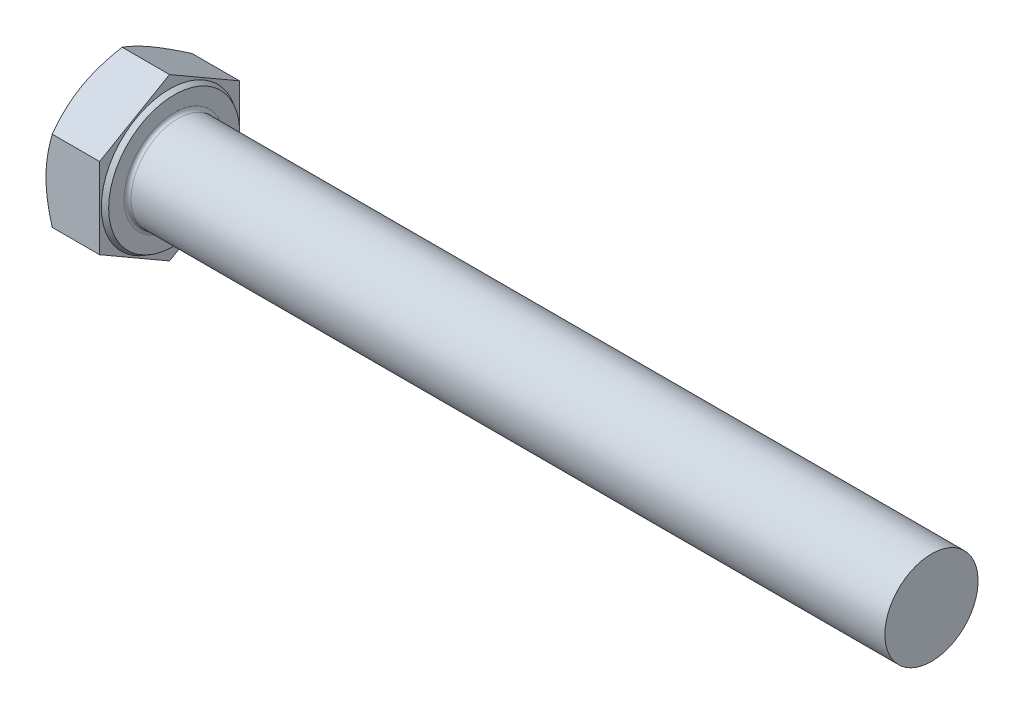
SolidWorks part; units mm, degrees
ref_plane "前视" through (0, 0, 0) normal (0, 0, 1) x (1, 0, 0)
ref_plane "上视" through (0, 0, 0) normal (0, 1, 0) x (1, 0, 0)
ref_plane "右视" through (0, 0, 0) normal (1, 0, 0) x (0, 0, -1)
sketch "草图1" plane through (0, 0, 0) normal (1, 0, 0) x (0, 0, -1)
  line L0 (12, 6.9282) -> (12, -6.9282)
  line L1 (-12, 6.9282) -> (-12, -6.9282)
  line L2 (12, -6.9282) -> (0, -13.8564)
  line L3 (0, -13.8564) -> (-12, -6.9282)
  line L4 (12, 6.9282) -> (0, 13.8564)
  line L5 (0, 13.8564) -> (-12, 6.9282)
  circle A0 centre (0, 0) radius 13.375 construction
  dimension "e" = 26.75
  dimension "s" = 24
  dimension "D2" = 120
  dimension "D3" = 12
  dimension "D4" = 12
  dimension "D5" = 12
extrude "基体-拉伸" add sketch "草图1" along normal blind 10
sketch "草图2" plane through (0, 0, 0) normal (0, 0, 1) x (1, 0, 0)
  line L0 (0, 6.9282) -> (0, -6.9282) construction
  line L1 (0, 0) -> (140, 0)
  line L2 (0, 0) -> (0, 8)
  line L3 (0, 8) -> (96, 8)
  line L4 (140, 0) -> (140, 6.268)
  line L5 (10, 13.8564) -> (10, 6.9282) construction
  line L7 (0, 0) -> (156, 0) construction
  line L8 (140, -6.268) -> (96, -8) construction
  line L9 (0, -8) -> (96, -8) construction
  line L10 (12, 8) -> (12, 0) construction
  line L11 (96, 15.24) -> (96, -1.27) construction
  line L12 (10, 6.9282) -> (10, -6.9282) construction
  line L13 (96, 8) -> (140, 8)
  line L14 (140, 8) -> (140, 6.268)
  dimension "l" = 130
  dimension "d" = 16
  dimension "Minor_dia" = 12.536
  dimension "p" = 2
  dimension "b" = 44
  dimension "ds" = 16
revolve "凸台-旋转1" add sketch "草图2" angle 360 about L7
cosmetic thread "螺旋线1" parameters "Thread_length"=44, "Thread_minor"=12.536
sketch "草图3" plane through (0, 0, 0) normal (0, 0, 1) x (1, 0, 0)
  line L0 (0, 12) -> (3.9585, 18.8564)
  line L1 (0, 13.8564) -> (0, 6.9282) construction
  line L2 (3.9585, 18.8564) -> (3.9585, 23.8564)
  line L3 (3.9585, 23.8564) -> (-10, 23.8564)
  line L4 (-10, 23.8564) -> (-10, 12)
  line L5 (-10, 12) -> (0, 12)
  line L6 (0, 0) -> (99.06, 0) construction
  line L7 (10, 13.8564) -> (0, 13.8564) construction
  dimension "D1" = 12
  dimension "D2" = 5
  dimension "D3" = 10
  dimension "D4" = 5
  dimension "Head_ch_ang" = 30
revolve "切除-旋转1" cut sketch "草图3" angle 360 about L6
sketch "草图4" plane through (0, 0, 0) normal (0, 0, 1) x (1, 0, 0)
  line L0 (10, 0) -> (10, 11.245) construction
  line L2 (10, -8) -> (10, 8) construction
  line L3 (10, 13.8564) -> (10, 6.9282) construction
  line L4 (10, 11.245) -> (9.2, 11.7069)
  line L5 (0, 0) -> (95.25, 0) construction
  line L6 (0, 0) -> (156, 0) construction
  line L9 (9.2, 11.7069) -> (9.2, 13.8564)
  line L10 (10, 13.8564) -> (1.0718, 13.8564) construction
  line L11 (9.2, 13.8564) -> (10, 13.8564)
  line L12 (10, 13.8564) -> (10, 11.245)
  dimension "D1" = 120
  dimension "c" = 0.8
  dimension "dw" = 22.49
revolve "切除-旋转3" cut sketch "草图4" angle 360 about L5
fillet "圆角" radius 0.6 1 edges at (10, 0, -8)
sketch "草图6" plane through (0, 0, 0) normal (0, 0, 1) x (1, 0, 0)
  line L0 (0, 0) -> (140, 0) construction
  line L1 (140, -8) -> (140, 8) construction
  line L2 (140, 0) -> (140, 8) construction
  line L4 (139, 8) -> (141, 8)
  line L5 (139, 8) -> (140, 6.2679)
  line L6 (140, 6.2679) -> (141, 8)
  dimension "D1" = 2
revolve "切除-旋转4" [suppressed] cut sketch "草图6" angle 360 about L0
pattern_linear "阵列(线性)1" [suppressed]
